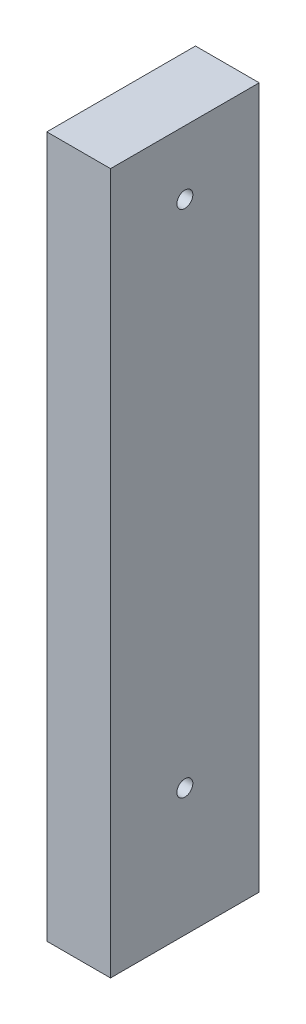
SolidWorks part; units mm, degrees
material "Pine"
ref_plane "Front Plane" through (0, 0, 0) normal (0, 0, 1) x (1, 0, 0)
ref_plane "Top Plane" through (0, 0, 0) normal (0, 1, 0) x (1, 0, 0)
ref_plane "Right Plane" through (0, 0, 0) normal (1, 0, 0) x (0, 0, -1)
sketch "Sketch1" plane through (0, 0, 0) normal (0, 1, 0) x (1, 0, 0)
  line L1 (0, 0) -> (38.1, 0)
  line L2 (0, 0) -> (0, 88.9)
  line L3 (0, 88.9) -> (38.1, 88.9)
  line L4 (38.1, 0) -> (38.1, 88.9)
  dimension "D1" = 38.1
  dimension "D2" = 88.9
extrude "Boss-Extrude1" add sketch "Sketch1" along normal blind 419.1
sketch "Sketch2" plane through (0, 0, 0) normal (-1, 0, 0) x (0, 0, 1)
  line L4 (-88.9, 0) -> (0, 0)
  line L5 (0, 0) -> (0, 419.1)
  line L6 (0, 419.1) -> (-88.9, 419.1)
  line L7 (-88.9, 419.1) -> (-88.9, 0)
  line L8 (-88.9, 0) -> (0, 0)
  line L9 (0, 0) -> (0, 419.1)
  line L10 (0, 419.1) -> (-88.9, 419.1)
  line L11 (-88.9, 419.1) -> (-88.9, 0)
  circle A0 centre (-44.45, 381) radius 4.7625
  circle A1 centre (-44.45, 76.2) radius 4.7625
  dimension "D2" = 9.525
  dimension "D5" = 9.525
  dimension "D3" = 44.45
  dimension "D4" = 38.1
  dimension "D6" = 76.2
  dimension "D7" = 44.45
  dimension "D1" = 0
extrude "Cut-Extrude1" cut sketch "Sketch2" against normal blind 38.1 flip side to cut
